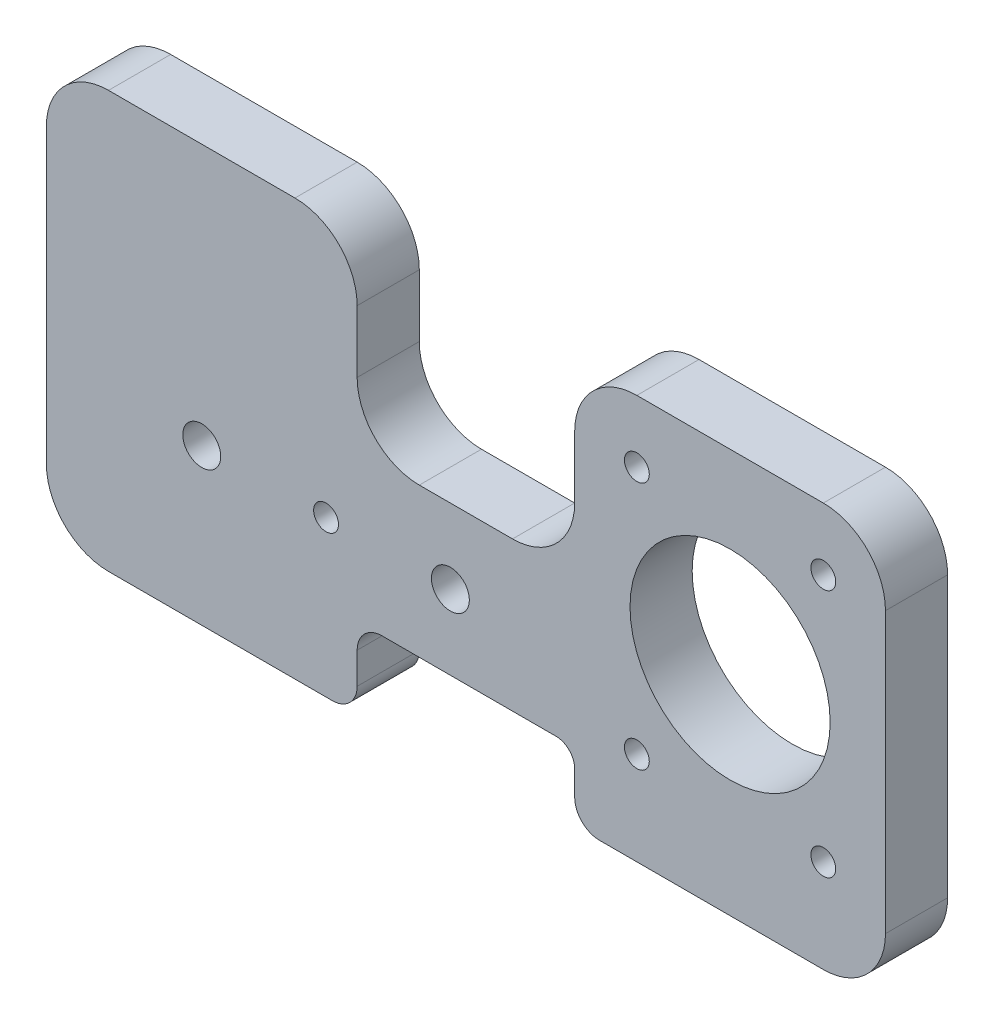
SolidWorks part; units mm, degrees
ref_plane "Front Plane" through (0, 0, 0) normal (0, 0, 1) x (1, 0, 0)
ref_plane "Top Plane" through (0, 0, 0) normal (0, 1, 0) x (1, 0, 0)
ref_plane "Right Plane" through (0, 0, 0) normal (1, 0, 0) x (0, 0, -1)
sketch "Model" plane through (0, 0, 0) normal (0, 0, 1) x (1, 0, 0)
  line L0 (106.9106, -1) -> (106.9106, 3)
  line L1 (75.9106, 6) -> (103.9106, 6)
  line L2 (71.9106, 2) -> (71.9106, -3.0349)
  line L3 (67.9106, -7.0349) -> (31.9106, -7.0349)
  line L4 (21.9106, 2.9651) -> (21.9106, 50)
  line L5 (31.9106, 60) -> (61.9106, 60)
  line L6 (71.9106, 50) -> (71.9106, 40)
  line L7 (96.9106, 30) -> (81.9106, 30)
  line L8 (106.9106, 50) -> (106.9106, 40)
  line L9 (146.9106, 60) -> (116.9106, 60)
  line L10 (156.9106, 5) -> (156.9106, 50)
  line L11 (146.9106, -5) -> (110.9106, -5)
  circle A0 centre (66.9106, 18) radius 2
  circle A1 centre (46.9106, 18) radius 3.05
  circle A2 centre (116.9106, 10) radius 2
  circle A3 centre (146.9106, 10) radius 2
  circle A4 centre (146.9106, 50) radius 2
  circle A5 centre (116.9106, 50) radius 2
  circle A6 centre (131.9106, 30) radius 6.75
  circle A7 centre (86.9106, 18) radius 3.05
  arc A8 (106.9106, -1) -> (110.9106, -5) centre (110.9106, -1) ccw
  arc A9 (106.9106, 3) -> (103.9106, 6) centre (103.9106, 3) ccw
  arc A10 (75.9106, 6) -> (71.9106, 2) centre (75.9106, 2) ccw
  arc A11 (67.9106, -7.0349) -> (71.9106, -3.0349) centre (67.9106, -3.0349) ccw
  arc A12 (21.9106, 2.9651) -> (31.9106, -7.0349) centre (31.9106, 2.9651) ccw
  arc A13 (31.9106, 60) -> (21.9106, 50) centre (31.9106, 50) ccw
  arc A14 (71.9106, 50) -> (61.9106, 60) centre (61.9106, 50) ccw
  arc A15 (71.9106, 40) -> (81.9106, 30) centre (81.9106, 40) ccw
  arc A16 (96.9106, 30) -> (106.9106, 40) centre (96.9106, 40) ccw
  arc A17 (116.9106, 60) -> (106.9106, 50) centre (116.9106, 50) ccw
  arc A18 (156.9106, 50) -> (146.9106, 60) centre (146.9106, 50) ccw
  arc A19 (146.9106, -5) -> (156.9106, 5) centre (146.9106, 5) ccw
extrude "Boss-Extrude1" add sketch "Model" along normal blind 10
sketch "Sketch2" plane through (0, 0, 10) normal (0, 0, 1) x (1, 0, 0)
  circle A0 centre (131.9106, 30) radius 16.1
  dimension "D1" = 32.2
extrude "Cut-Extrude1" cut sketch "Sketch2" against normal blind 10
sketch "Sketch3" plane through (0, 0, 10) normal (0, 0, 1) x (1, 0, 0)
  text T0 "Copyright © Adarsh Belavatagi and Manikanta Pujar 2018.\r\nThis documentation describes Open Hardware and is licensed under the CERN OHL v. 1.2.\r\nYou may redistribute and modify this documentation under the terms of the CERN OHL v.1.2.\r\n(http://ohwr.org/cernohl). This documentation is distributed WITHOUT ANY EXPRESS OR\r\nIMPLIED WARRANTY, INCLUDING OF MERCHANTABILITY, SATISFACTORY QUALITY AND FITNESS FOR A PARTICULAR PURPOSE.\r\nPlease see the CERN OHL v.1.2 for applicable conditions\r\n\r\nThe full text of the license is available in LICENSE.txt(https://github.com/AdarshBelavatagi/Maudslay/blob/master/LICENSE.txt)\r\n\r\n"
